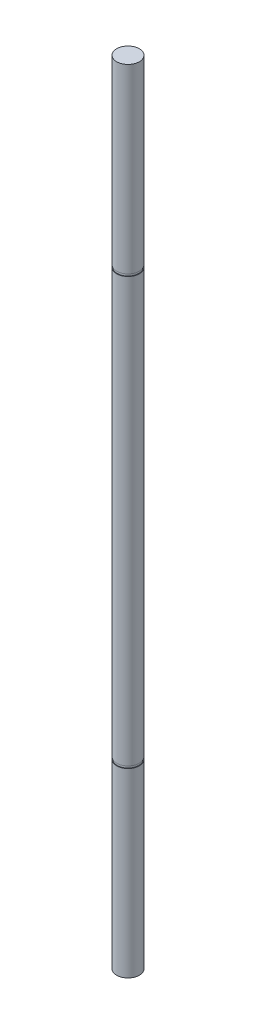
SolidWorks part; units mm, degrees
ref_plane "前视" through (0, 0, 0) normal (0, 0, 1) x (1, 0, 0)
ref_plane "上视" through (0, 0, 0) normal (0, 1, 0) x (1, 0, 0)
ref_plane "右视" through (0, 0, 0) normal (1, 0, 0) x (0, 0, -1)
sketch "草图1" plane through (0, 0, 0) normal (0, 1, 0) x (1, 0, 0)
  circle A0 centre (0, 0) radius 4
  dimension "D1" = 8
extrude "凸台-拉伸1" add sketch "草图1" along normal mid plane 280
sketch "草图3" plane through (0, 0, 0) normal (1, 0, 0) x (0, 0, -1)
  line L0 (0, 140) -> (0, -140) construction
  line L1 (3.8, 75.8) -> (8.8, 75.8)
  line L2 (3.8, 75.8) -> (3.8, 75)
  line L3 (3.8, 75) -> (8.8, 75)
  line L4 (8.8, 75.8) -> (8.8, 75)
  line L5 (3.8, 75.8) -> (8.8, 75) construction
  line L6 (3.8, 75) -> (8.8, 75.8) construction
  point P0 (6.3, 75.4)
  dimension "D1" = 75
  dimension "D2" = 0.8
  dimension "D3" = 3.8
  dimension "D4" = 5
revolve "切除-旋转1" cut sketch "草图3" angle 360 about axis through (0, 140, 0) along (0, -1, 0)
ref_plane "基准面1" through (0, 0, 0) normal (0, 1, 0) x (1, 0, 0)
mirror "镜向1" about plane through (0, 0, 0) normal (0, 1, 0) of "切除-旋转1"
